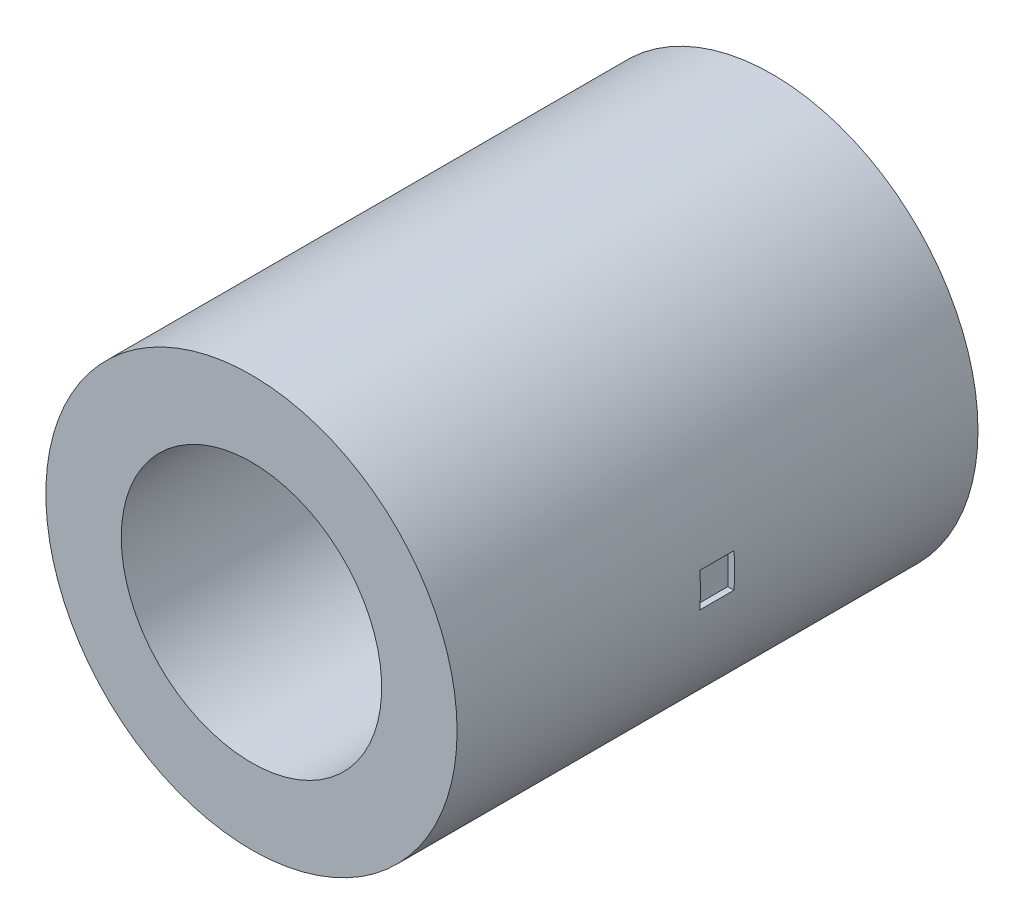
SolidWorks part; units mm, degrees
ref_plane "Alzado" through (0, 0, 0) normal (0, 0, 1) x (1, 0, 0)
ref_plane "Planta" through (0, 0, 0) normal (0, 1, 0) x (1, 0, 0)
ref_plane "Vista lateral" through (0, 0, 0) normal (1, 0, 0) x (0, 0, -1)
sketch "Croquis1" plane through (0, 0, 0) normal (0, 0, 1) x (1, 0, 0)
  circle A0 centre (0, 0) radius 3
  circle A1 centre (0, 0) radius 1.9
  dimension "D1" = 6
  dimension "D2" = 3.8
extrude "Saliente-Extruir1" add sketch "Croquis1" along normal blind 7.6
sketch "Croquis2" plane through (0, 0, 7.6) normal (0, 0, 1) x (1, 0, 0)
  line L1 (0.3834, 2.4903) -> (-0.2175, 2.4903)
  line L2 (0.3834, 2.4903) -> (0.3834, 2.9921)
  line L3 (0.3834, 2.9921) -> (-0.2175, 2.9921)
  line L4 (-0.2175, 2.4903) -> (-0.2175, 2.9921)
  circle A0 centre (0, 0) radius 3 construction
ref_plane "Plano1" through (-3, 0, 0) normal (-1, 0, 0) x (0, 0, 1)
sketch "Croquis3" plane through (-3, 0, 0) normal (-1, 0, 0) x (0, 0, 1)
  line L0 (0, 0) -> (7.6, 0) construction
  line L1 (3.55, 0.25) -> (4.05, 0.25)
  line L2 (3.55, 0.25) -> (3.55, -0.25)
  line L3 (3.55, -0.25) -> (4.05, -0.25)
  line L4 (4.05, 0.25) -> (4.05, -0.25)
  line L5 (7.6, -3) -> (7.6, 3) construction
  line L6 (3.8, 3) -> (3.8, -3) construction
  line L7 (7.6, 3) -> (0, 3) construction
  line L8 (0, -3) -> (7.6, -3) construction
  point P15 (3.8, 0.25)
  point P16 (4.05, 0)
  dimension "D1" = 0.5
  dimension "D2" = 0.5
extrude "Cortar-Extruir1" cut sketch "Croquis3" against normal blind 0.1
mirror "Simetría1" about plane through (0, 0, 0) normal (1, 0, 0) of "Cortar-Extruir1"
